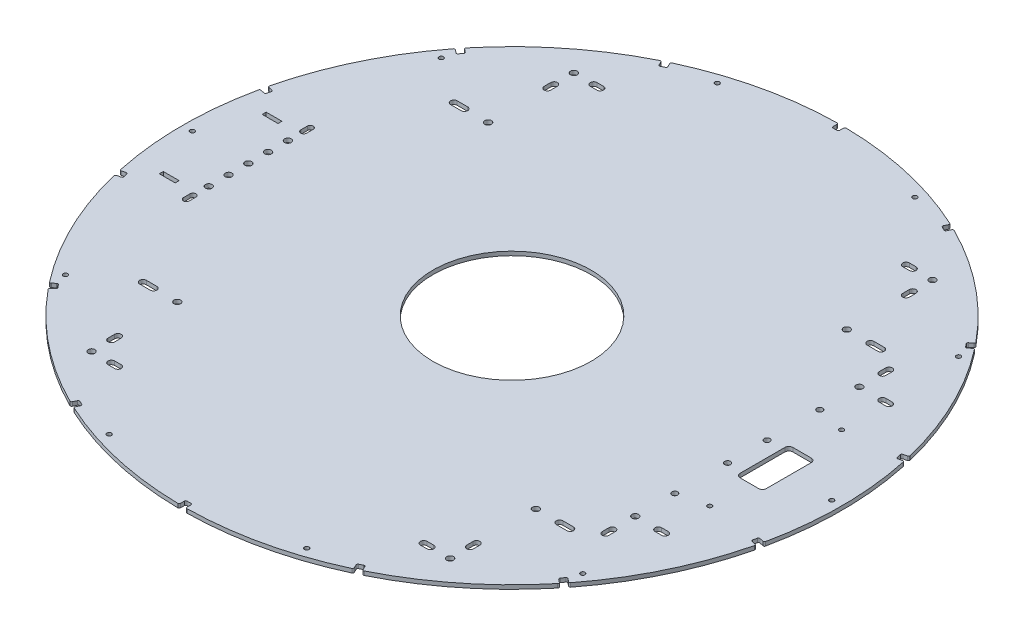
SolidWorks part; units mm, degrees
ref_plane "Front Plane" through (0, 0, 0) normal (0, 0, 1) x (1, 0, 0)
ref_plane "Top Plane" through (0, 0, 0) normal (0, 1, 0) x (1, 0, 0)
ref_plane "Right Plane" through (0, 0, 0) normal (1, 0, 0) x (0, 0, -1)
sketch "Sketch1" plane through (0, 0, 0) normal (0, 1, 0) x (1, 0, 0)
  circle A0 centre (0, 0) radius 250
extrude "Boss-Extrude1" add sketch "Sketch1" along normal blind 3
sketch "Sketch11" plane through (0, 3, 0) normal (0, 1, 0) x (1, 0, 0)
  line L1 (1.5, 245) -> (-1.5, 245)
  line L2 (2.5, 246) -> (2.5, 255)
  line L3 (2.5, 255) -> (-2.5, 255)
  line L4 (-2.5, 246) -> (-2.5, 255)
  line L5 (2.5, 245) -> (-2.5, 255) construction
  line L6 (2.5, 255) -> (-2.5, 245) construction
  circle A0 centre (0, 0) radius 250 construction
  arc A1 (2.5, 246) -> (1.5, 245) centre (1.5, 246) cw
  arc A2 (-1.5, 245) -> (-2.5, 246) centre (-1.5, 246) cw
  point P0 (0, 250)
  dimension "D3" = 1
  dimension "D1" = 10
  dimension "D2" = 5
extrude "Cut-Extrude5" cut sketch "Sketch11" against normal blind 4
fillet "Fillet1" radius 1 2 edges at (2.5, 1.5, -249.9875) (-2.5, 1.5, -249.9875)
pattern_circular "CirPattern1" count 14 over 360 about axis through (0, 0, 0) along (0, 1, 0) of "Cut-Extrude5", "Fillet1"
sketch "Sketch20" plane through (0, 0, 0) normal (0, -1, 0) x (1, 0, 0)
  line L0 (-166.5, -117.9) -> (-148.647, -117.9) construction
  line L1 (-162, -117.9) -> (-154, -117.9) construction
  line L2 (-162, -115.4) -> (-154, -115.4)
  line L3 (-162, -120.4) -> (-154, -120.4)
  line L4 (0, -1.65) -> (0, 1.65) construction
  line L5 (166.5, -117.9) -> (148.647, -117.9) construction
  line L6 (162, -117.9) -> (154, -117.9) construction
  line L7 (162, -115.4) -> (154, -115.4)
  line L8 (162, -120.4) -> (154, -120.4)
  line L9 (1.65, 0) -> (-1.65, 0) construction
  line L10 (162, 117.9) -> (154, 117.9) construction
  line L11 (162, 115.4) -> (154, 115.4)
  line L12 (162, 120.4) -> (154, 120.4)
  line L13 (-162, 117.9) -> (-154, 117.9) construction
  line L14 (-162, 115.4) -> (-154, 115.4)
  line L15 (-162, 120.4) -> (-154, 120.4)
  line L16 (-166.5, 117.9) -> (-148.647, 117.9) construction
  line L17 (166.5, 117.9) -> (148.647, 117.9) construction
  arc A0 (-164, -115.4) -> (-164, -120.4) centre (-164, -117.9) ccw construction
  arc A1 (-162, -115.4) -> (-162, -120.4) centre (-162, -117.9) ccw
  arc A2 (-154, -120.4) -> (-154, -115.4) centre (-154, -117.9) ccw
  arc A3 (162, -115.4) -> (162, -120.4) centre (162, -117.9) cw
  arc A4 (154, -120.4) -> (154, -115.4) centre (154, -117.9) cw
  arc A5 (162, 115.4) -> (162, 120.4) centre (162, 117.9) ccw
  arc A6 (154, 120.4) -> (154, 115.4) centre (154, 117.9) ccw
  arc A7 (-162, 115.4) -> (-162, 120.4) centre (-162, 117.9) cw
  arc A8 (-154, 120.4) -> (-154, 115.4) centre (-154, 117.9) cw
  point P8 (-158, -117.9)
  point P20 (158, -117.9)
  point P29 (158, 117.9)
  point P36 (-158, 117.9)
  dimension "D1" = 2.5
  dimension "D2" = 8
  dimension "D3" = 158
extrude "Cut-Extrude14" cut sketch "Sketch20" against normal blind 14
sketch "Sketch22" plane through (0, 3, 0) normal (0, 1, 0) x (1, 0, 0)
  line L0 (-1.65, 0) -> (1.65, 0) construction
  line L1 (0, -1.65) -> (0, 1.65) construction
  circle A0 centre (-136, -117.9) radius 2.5
  circle A1 centre (-136, 117.9) radius 2.5
  circle A2 centre (136, 117.9) radius 2.5
  circle A3 centre (136, -117.9) radius 2.5
  circle A4 centre (-136, 182.9) radius 2.5
  circle A5 centre (136, 182.9) radius 2.5
  circle A6 centre (-136, -182.9) radius 2.5
  circle A7 centre (136, -182.9) radius 2.5
  dimension "D1" = 2
extrude "Cut-Extrude16" cut sketch "Sketch22" against normal blind 14
sketch "Sketch26" plane through (0, 3, 0) normal (0, 1, 0) x (1, 0, 0)
  line L0 (-136, 162.9) -> (-136, 167.9) construction
  line L1 (-138.5, 162.9) -> (-138.5, 167.9)
  line L2 (-133.5, 162.9) -> (-133.5, 167.9)
  line L3 (-116, 182.9) -> (-121, 182.9) construction
  line L4 (-116, 180.4) -> (-121, 180.4)
  line L5 (-116, 185.4) -> (-121, 185.4)
  line L6 (0, -1.65) -> (0, 1.65) construction
  line L7 (116, 182.9) -> (121, 182.9) construction
  line L8 (116, 180.4) -> (121, 180.4)
  line L9 (116, 185.4) -> (121, 185.4)
  line L10 (136, 162.9) -> (136, 167.9) construction
  line L11 (138.5, 162.9) -> (138.5, 167.9)
  line L12 (133.5, 162.9) -> (133.5, 167.9)
  line L13 (-1.65, 0) -> (1.65, 0) construction
  line L14 (116, -182.9) -> (121, -182.9) construction
  line L15 (116, -180.4) -> (121, -180.4)
  line L16 (116, -185.4) -> (121, -185.4)
  line L17 (136, -162.9) -> (136, -167.9) construction
  line L18 (138.5, -162.9) -> (138.5, -167.9)
  line L19 (133.5, -162.9) -> (133.5, -167.9)
  line L20 (-136, -162.9) -> (-136, -167.9) construction
  line L21 (-138.5, -162.9) -> (-138.5, -167.9)
  line L22 (-133.5, -162.9) -> (-133.5, -167.9)
  line L23 (-116, -182.9) -> (-121, -182.9) construction
  line L24 (-116, -180.4) -> (-121, -180.4)
  line L25 (-116, -185.4) -> (-121, -185.4)
  arc A0 (-138.5, 162.9) -> (-133.5, 162.9) centre (-136, 162.9) ccw
  arc A1 (-133.5, 167.9) -> (-138.5, 167.9) centre (-136, 167.9) ccw
  circle A2 centre (-136, 182.9) radius 2.5 construction
  arc A3 (-116, 180.4) -> (-116, 185.4) centre (-116, 182.9) ccw
  arc A4 (-121, 185.4) -> (-121, 180.4) centre (-121, 182.9) ccw
  arc A5 (116, 180.4) -> (116, 185.4) centre (116, 182.9) cw
  arc A6 (121, 185.4) -> (121, 180.4) centre (121, 182.9) cw
  arc A7 (138.5, 162.9) -> (133.5, 162.9) centre (136, 162.9) cw
  arc A8 (133.5, 167.9) -> (138.5, 167.9) centre (136, 167.9) cw
  arc A9 (116, -180.4) -> (116, -185.4) centre (116, -182.9) ccw
  arc A10 (121, -185.4) -> (121, -180.4) centre (121, -182.9) ccw
  arc A11 (138.5, -162.9) -> (133.5, -162.9) centre (136, -162.9) ccw
  arc A12 (133.5, -167.9) -> (138.5, -167.9) centre (136, -167.9) ccw
  arc A13 (-138.5, -162.9) -> (-133.5, -162.9) centre (-136, -162.9) cw
  arc A14 (-133.5, -167.9) -> (-138.5, -167.9) centre (-136, -167.9) cw
  arc A15 (-116, -180.4) -> (-116, -185.4) centre (-116, -182.9) cw
  arc A16 (-121, -185.4) -> (-121, -180.4) centre (-121, -182.9) cw
  point P3 (-136, 165.4)
  point P12 (-118.5, 182.9)
  point P21 (118.5, 182.9)
  point P28 (136, 165.4)
  point P37 (118.5, -182.9)
  point P44 (136, -165.4)
  point P51 (-136, -165.4)
  point P58 (-118.5, -182.9)
  dimension "D1" = 2.5
  dimension "D4" = 2.5
  dimension "D2" = 5
  dimension "D3" = 17.5
  dimension "D5" = 5
  dimension "D6" = 17.5
extrude "Cut-Extrude19" cut sketch "Sketch26" against normal blind 4
sketch "Sketch28" plane through (0, 3, 0) normal (0, 1, 0) x (1, 0, 0)
  line L0 (-1.65, 0) -> (1.65, 0) construction
  circle A0 centre (-200, 0) radius 2.5
  circle A1 centre (-200, -15) radius 2.5
  circle A2 centre (-200, -30) radius 2.5
  circle A3 centre (-200, 30) radius 2.5
  circle A4 centre (-200, 15) radius 2.5
  dimension "D1" = 200
  dimension "D2" = 3
extrude "Cut-Extrude20" cut sketch "Sketch28" against normal blind 10
sketch "Sketch29" plane through (0, 3, 0) normal (0, 1, 0) x (1, 0, 0)
  line L0 (-200, 42) -> (-200, 47) construction
  line L1 (-202.2, 42) -> (-202.2, 47)
  line L2 (-197.8, 42) -> (-197.8, 47)
  line L3 (-1.65, 0) -> (1.65, 0) construction
  line L4 (-200, -42) -> (-200, -47) construction
  line L5 (-202.2, -42) -> (-202.2, -47)
  line L6 (-197.8, -42) -> (-197.8, -47)
  arc A0 (-202.2, 42) -> (-197.8, 42) centre (-200, 42) ccw
  arc A1 (-197.8, 47) -> (-202.2, 47) centre (-200, 47) ccw
  arc A2 (-202.2, -42) -> (-197.8, -42) centre (-200, -42) cw
  arc A3 (-197.8, -47) -> (-202.2, -47) centre (-200, -47) cw
  point P3 (-200, 44.5)
  point P13 (-200, -44.5)
  dimension "D1" = 2.2
  dimension "D2" = 12
  dimension "D3" = 5
extrude "Cut-Extrude21" cut sketch "Sketch29" against normal blind 10
sketch "Sketch30" plane through (0, 3, 0) normal (0, 1, 0) x (1, 0, 0)
  line L0 (-1.65, 0) -> (1.65, 0) construction
  line L1 (-215, 37.5) -> (-227, 37.5)
  line L2 (-215, 37.5) -> (-215, 40.5)
  line L3 (-215, 40.5) -> (-227, 40.5)
  line L4 (-227, 37.5) -> (-227, 40.5)
  line L5 (-215, 37.5) -> (-227, 40.5) construction
  line L6 (-215, 40.5) -> (-227, 37.5) construction
  line L7 (-215, -40.5) -> (-227, -37.5) construction
  line L8 (-215, -37.5) -> (-227, -40.5) construction
  line L9 (-227, -37.5) -> (-227, -40.5)
  line L10 (-215, -40.5) -> (-227, -40.5)
  line L11 (-215, -37.5) -> (-215, -40.5)
  line L12 (-215, -37.5) -> (-227, -37.5)
  circle A0 centre (-200, 30) radius 2.5 construction
  point P0 (-221, 39)
  point P13 (-221, -39)
  dimension "D1" = 12
  dimension "D2" = 3
  dimension "D3" = 9
  dimension "D4" = 21
extrude "Cut-Extrude22" cut sketch "Sketch30" against normal blind 10
sketch "Sketch31" plane through (0, 3, 0) normal (0, 1, 0) x (1, 0, 0)
  circle A0 centre (178.5, 85) radius 2.5
  circle A1 centre (178.5, -85) radius 2.5
extrude "Cut-Extrude23" cut sketch "Sketch31" against normal blind 10
sketch "Sketch32" plane through (0, 3, 0) normal (0, 1, 0) x (1, 0, 0)
  line L0 (178.5, 107.5) -> (178.5, 102.5) construction
  line L1 (181, 107.5) -> (181, 102.5)
  line L2 (176, 107.5) -> (176, 102.5)
  line L3 (201, 85) -> (196, 85) construction
  line L4 (201, 82.5) -> (196, 82.5)
  line L5 (201, 87.5) -> (196, 87.5)
  line L6 (-1.65, 0) -> (1.65, 0) construction
  line L7 (201, -85) -> (196, -85) construction
  line L8 (201, -82.5) -> (196, -82.5)
  line L9 (201, -87.5) -> (196, -87.5)
  line L10 (178.5, -107.5) -> (178.5, -102.5) construction
  line L11 (181, -107.5) -> (181, -102.5)
  line L12 (176, -107.5) -> (176, -102.5)
  arc A0 (181, 107.5) -> (176, 107.5) centre (178.5, 107.5) ccw
  arc A1 (176, 102.5) -> (181, 102.5) centre (178.5, 102.5) ccw
  circle A2 centre (178.5, 85) radius 2.5 construction
  arc A3 (201, 82.5) -> (201, 87.5) centre (201, 85) ccw
  arc A4 (196, 87.5) -> (196, 82.5) centre (196, 85) ccw
  arc A5 (201, -82.5) -> (201, -87.5) centre (201, -85) cw
  arc A6 (196, -87.5) -> (196, -82.5) centre (196, -85) cw
  arc A7 (181, -107.5) -> (176, -107.5) centre (178.5, -107.5) cw
  arc A8 (176, -102.5) -> (181, -102.5) centre (178.5, -102.5) cw
  point P3 (178.5, 105)
  point P12 (198.5, 85)
  point P21 (198.5, -85)
  point P28 (178.5, -105)
  dimension "D1" = 2.5
  dimension "D3" = 2.5
  dimension "D2" = 20
  dimension "D4" = 20
  dimension "D5" = 5
  dimension "D6" = 5
extrude "Cut-Extrude24" cut sketch "Sketch32" against normal blind 10
sketch "Sketch33" plane through (0, 3, 0) normal (0, 1, 0) x (1, 0, 0)
  line L0 (-1.65, 0) -> (1.65, 0) construction
  circle A0 centre (178.5, 55) radius 2.2
  circle A1 centre (178.5, 85) radius 2.5 construction
  circle A2 centre (178.5, 15) radius 2.2
  circle A3 centre (178.5, -15) radius 2.2
  circle A4 centre (178.5, -55) radius 2.2
  dimension "D1" = 30
extrude "Cut-Extrude25" cut sketch "Sketch33" against normal blind 10
sketch "Sketch34" plane through (0, 3, 0) normal (0, 1, 0) x (1, 0, 0)
  line L1 (207, -20) -> (193, -20)
  line L2 (210, -17) -> (210, 17)
  line L3 (207, 20) -> (193, 20)
  line L4 (190, -17) -> (190, 17)
  line L5 (210, -20) -> (190, 20) construction
  line L6 (210, 20) -> (190, -20) construction
  arc A0 (190, -17) -> (193, -20) centre (193, -17) ccw
  arc A1 (207, -20) -> (210, -17) centre (207, -17) ccw
  arc A2 (210, 17) -> (207, 20) centre (207, 17) ccw
  arc A3 (193, 20) -> (190, 17) centre (193, 17) ccw
  point P0 (200, 0)
  dimension "D5" = 3
  dimension "D1" = 0
  dimension "D2" = 40
  dimension "D3" = 20
  dimension "D4" = 200
extrude "Cut-Extrude26" cut sketch "Sketch34" against normal blind 10
sketch "Sketch35" plane through (0, 3, 0) normal (0, 1, 0) x (1, 0, 0)
  circle A0 centre (0, 0) radius 242.5
  circle A1 centre (-242.5, 0) radius 1.7
extrude "Cut-Extrude27" cut sketch "Sketch35" against normal blind 10 contours A0 A1 | A0 A1
pattern_circular "CirPattern2" count 10 over 360 about axis through (0, 0, 0) along (0, 1, 0) of "Cut-Extrude27"
sketch "Sketch36" plane through (0, 3, 0) normal (0, 1, 0) x (1, 0, 0)
  circle A0 centre (0, 0) radius 60
extrude "Cut-Extrude28" cut sketch "Sketch36" against normal blind 10
sketch "Sketch37" plane through (0, 3, 0) normal (0, 1, 0) x (1, 0, 0)
  line L0 (207, 20) -> (193, 20) construction
  line L1 (193, -20) -> (207, -20) construction
  circle A0 centre (200, 50) radius 1.7
  circle A1 centre (200, -50) radius 1.7
  point P8 (0, 0)
  dimension "D1" = 30
  dimension "D2" = 30
extrude "Cut-Extrude29" cut sketch "Sketch37" against normal blind 3
